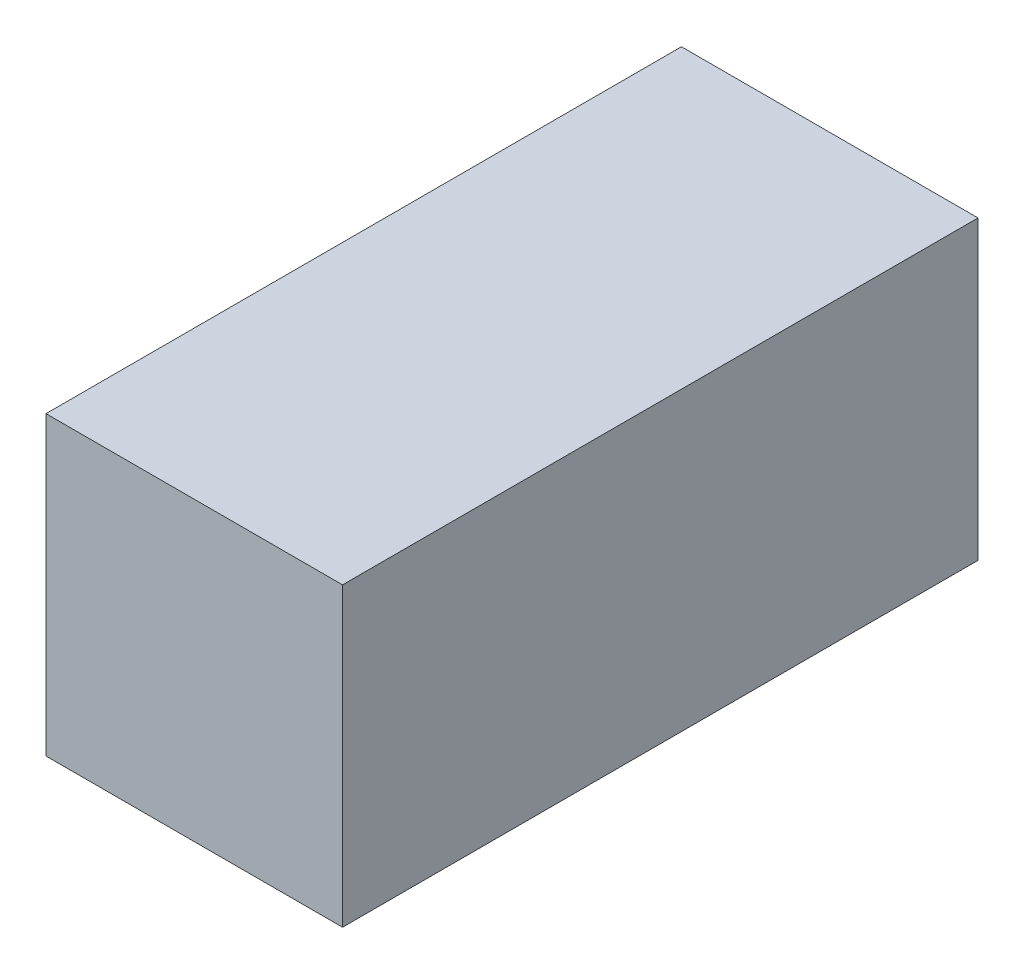
SolidWorks part; units mm, degrees
ref_plane "Front Plane" through (0, 0, 0) normal (0, 0, 1) x (1, 0, 0)
ref_plane "Top Plane" through (0, 0, 0) normal (0, 1, 0) x (1, 0, 0)
ref_plane "Right Plane" through (0, 0, 0) normal (1, 0, 0) x (0, 0, -1)
sketch "Sketch1" plane through (0, 0, 0) normal (0, 0, 1) x (1, 0, 0)
  line L1 (-22.225, 22.225) -> (22.225, 22.225)
  line L2 (-22.225, 22.225) -> (-22.225, -22.225)
  line L3 (-22.225, -22.225) -> (22.225, -22.225)
  line L4 (22.225, 22.225) -> (22.225, -22.225)
  line L5 (-22.225, 22.225) -> (22.225, -22.225) construction
  line L6 (-22.225, -22.225) -> (22.225, 22.225) construction
  point P0 (0, 0)
  dimension "D1" = 44.45
extrude "Boss-Extrude1" add sketch "Sketch1" along normal blind 95.25
